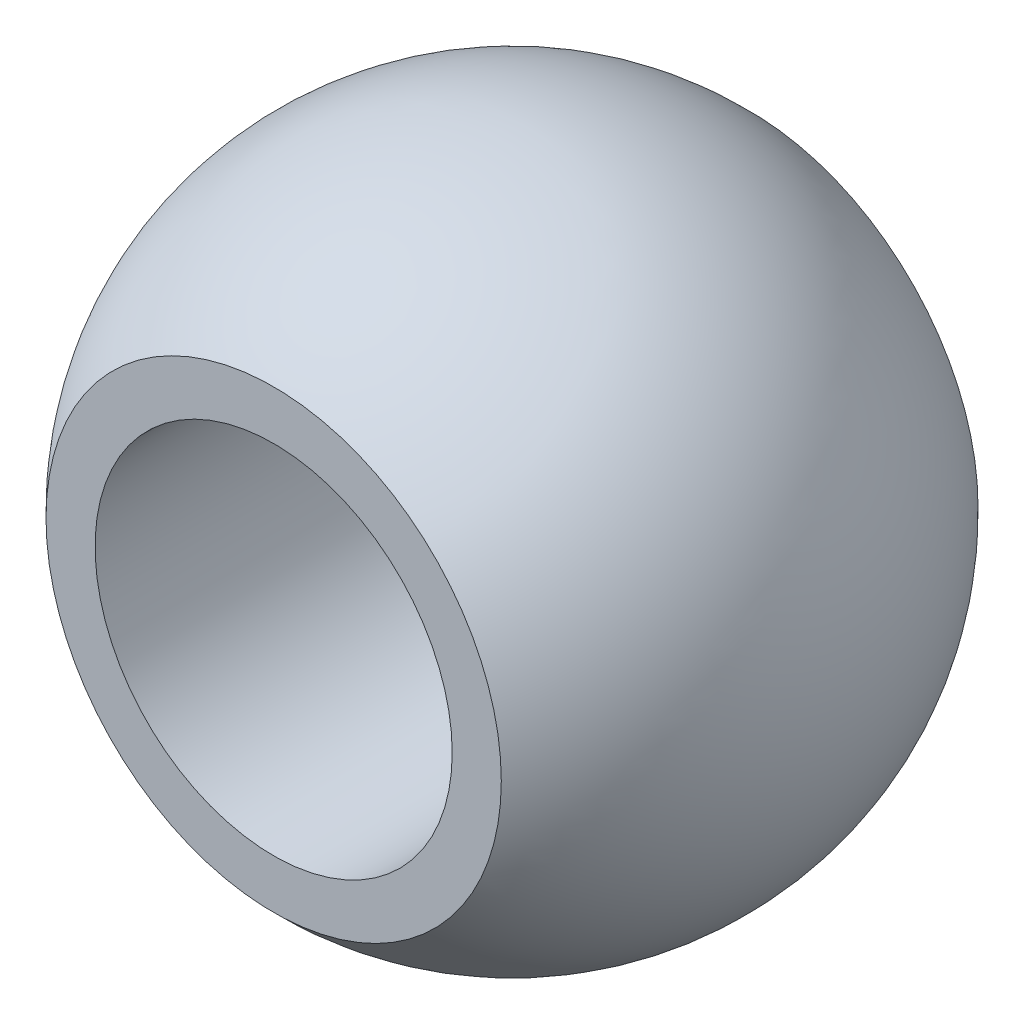
SolidWorks part; units mm, degrees
ref_plane "정면" through (0, 0, 0) normal (0, 0, 1) x (1, 0, 0)
ref_plane "윗면" through (0, 0, 0) normal (0, 1, 0) x (1, 0, 0)
ref_plane "우측면" through (0, 0, 0) normal (1, 0, 0) x (0, 0, -1)
sketch "스케치1" plane through (0, 0, 0) normal (0, 0, 1) x (1, 0, 0)
  line L0 (0, 11.075) -> (0, -11.075)
  arc A0 (0, -11.075) -> (0, 11.075) centre (0, 0) ccw
revolve "회전1" add sketch "스케치1" angle 360 about L0
sketch "스케치2" plane through (0, 0, 0) normal (0, 0, 1) x (1, 0, 0)
  circle A0 centre (0, 0) radius 6
extrude "컷-돌출1" cut sketch "스케치2" against normal mid plane 150
sketch "스케치3" plane through (0, 0, 0) normal (0, 1, 0) x (1, 0, 0)
  line L1 (0, -9.3089) -> (0, -8.0089)
  line L2 (-6, -9.3089) -> (6, -9.3089) construction
  line L3 (0, -8.0089) -> (-12.8655, -8.0089)
  line L4 (-12.8655, -8.0089) -> (-12.8655, -13.8041)
  line L5 (-12.8655, -13.8041) -> (0, -13.8041)
  line L6 (0, -13.8041) -> (0, -9.3089)
revolve "컷-회전4" cut sketch "스케치3" angle 360 about L6
sketch "스케치5" plane through (0, 0, 0) normal (0, 1, 0) x (1, 0, 0)
  line L0 (0, 9.3089) -> (0, 8.0089)
  line L1 (6, 9.3089) -> (-6, 9.3089) construction
  line L2 (0, 8.0089) -> (-11.2429, 8.0089)
  line L3 (-11.2429, 8.0089) -> (-11.2429, 14.0188)
  line L4 (-11.2429, 14.0188) -> (0, 14.0188)
  line L5 (0, 14.0188) -> (0, 9.3089)
revolve "컷-회전5" cut sketch "스케치5" angle 360 about L5
